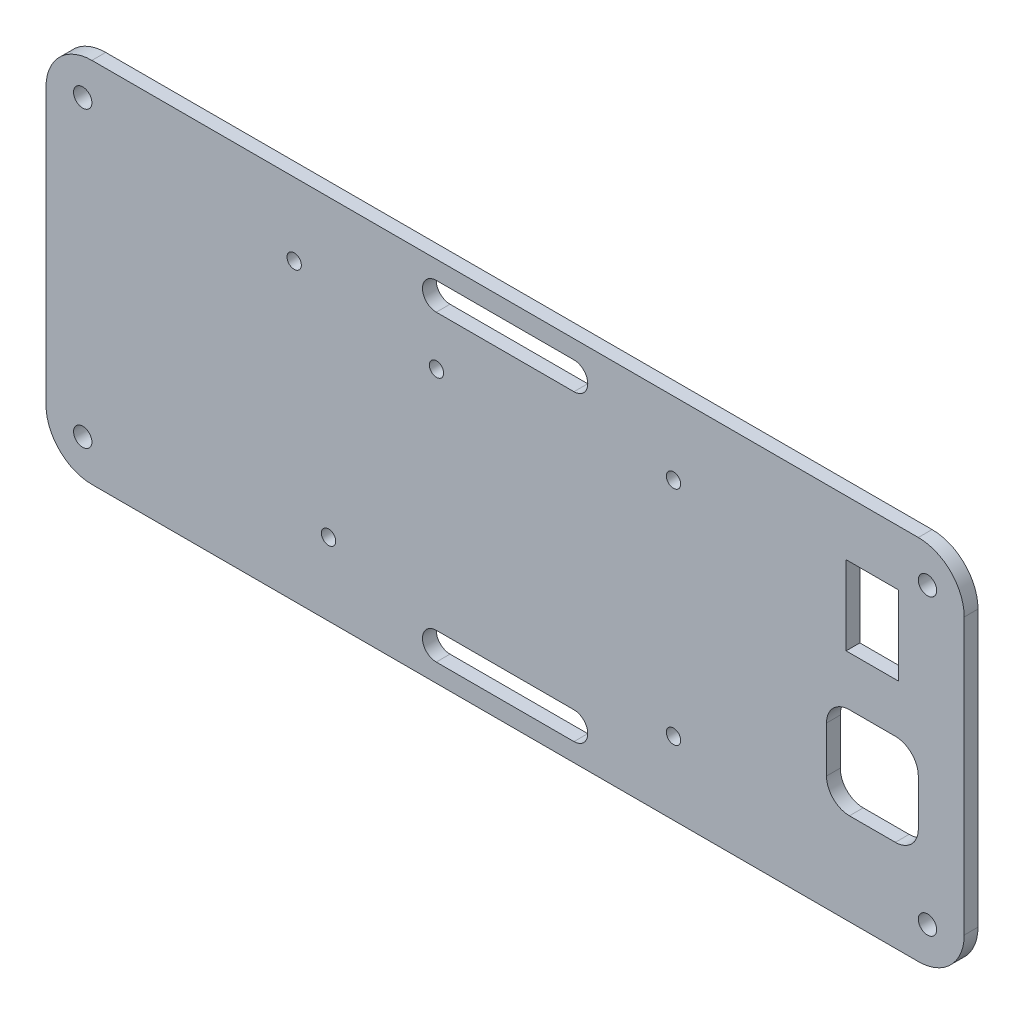
SolidWorks part; units mm, degrees
material "Mahogany"
ref_plane "Front Plane" through (0, 0, 0) normal (0, 0, 1) x (1, 0, 0)
ref_plane "Top Plane" through (0, 0, 0) normal (0, 1, 0) x (1, 0, 0)
ref_plane "Right Plane" through (0, 0, 0) normal (1, 0, 0) x (0, 0, -1)
sketch "Sketch1" plane through (0, 0, 0) normal (0, 0, 1) x (1, 0, 0)
  line L1 (-100, 40) -> (100, 40)
  line L2 (-100, 40) -> (-100, -40)
  line L3 (-100, -40) -> (100, -40)
  line L4 (100, 40) -> (100, -40)
  line L5 (-100, 40) -> (100, -40) construction
  line L6 (-100, -40) -> (100, 40) construction
  point P0 (0, 0)
  dimension "D1" = 80
  dimension "D2" = 200
extrude "Boss-Extrude1" add sketch "Sketch1" along normal blind 3
sketch "Sketch2" plane through (0, 0, 3) normal (0, 0, 1) x (1, 0, 0)
  line L0 (-100, 40) -> (-100, -40) construction
  line L1 (100, 40) -> (-100, 40) construction
  line L2 (0, 40) -> (0, -40) construction
  line L3 (-100, -40) -> (100, -40) construction
  line L4 (-100, 0) -> (100, 0) construction
  line L5 (100, -40) -> (100, 40) construction
  circle A0 centre (-92, 32) radius 2
  circle A1 centre (-92, -32) radius 2
  circle A2 centre (92, -32) radius 2
  circle A3 centre (92, 32) radius 2
  dimension "D1" = 4
  dimension "D2" = 8
  dimension "D3" = 8
extrude "Cut-Extrude1" cut sketch "Sketch2" against normal through all
fillet "Fillet1" radius 10 4 edges at (-100, -40, 1.5) (100, -40, 1.5) (100, 40, 1.5) (-100, 40, 1.5)
sketch "Sketch3" plane through (0, 0, 3) normal (0, 0, 1) x (1, 0, 0)
  circle A0 centre (36.6776, 24.1681) radius 1.5621
  circle A1 centre (36.6776, -24.1681) radius 1.5621
  circle A2 centre (-38.4556, -24.1681) radius 1.5621
  circle A3 centre (-45.9486, 24.1681) radius 1.5621
  circle A4 centre (-14.9479, 19.2896) radius 1.5621
extrude "Cut-Extrude2" cut sketch "Sketch3" against normal through all
sketch "Sketch4" plane through (0, 0, 3) normal (0, 0, 1) x (1, 0, 0)
  line L1 (70, 0) -> (90, 0)
  line L2 (70, 0) -> (70, -20)
  line L3 (70, -20) -> (90, -20)
  line L4 (90, 0) -> (90, -20)
  line L5 (70, 0) -> (90, -20) construction
  line L6 (70, -20) -> (90, 0) construction
  line L7 (100, -30) -> (100, 30) construction
  line L8 (-90, -40) -> (90, -40) construction
  point P0 (80, -10)
  dimension "D1" = 20
  dimension "D2" = 20
  dimension "D3" = 10
  dimension "D4" = 30
extrude "Cut-Extrude3" cut sketch "Sketch4" against normal through all
fillet "Fillet2" radius 5 4 edges at (90, -20, 1.5) (70, -20, 1.5) (70, 0, 1.5) (90, 0, 1.5)
sketch "Sketch5" plane through (0, 0, 3) normal (0, 0, 1) x (1, 0, 0)
  line L0 (-15, -33) -> (15, -33) construction
  line L1 (-15, -30) -> (15, -30)
  line L2 (-15, -36) -> (15, -36)
  line L3 (-90, -40) -> (90, -40) construction
  line L4 (-100, 0) -> (100, 0) construction
  line L5 (-100, 30) -> (-100, -30) construction
  line L6 (100, -30) -> (100, 30) construction
  line L7 (-15, 33) -> (15, 33) construction
  line L8 (-15, 30) -> (15, 30)
  line L9 (-15, 36) -> (15, 36)
  arc A0 (-15, -30) -> (-15, -36) centre (-15, -33) ccw
  arc A1 (15, -36) -> (15, -30) centre (15, -33) ccw
  arc A2 (-15, 30) -> (-15, 36) centre (-15, 33) cw
  arc A3 (15, 36) -> (15, 30) centre (15, 33) cw
  point P2 (0, -33)
  point P10 (0, -40)
  point P18 (0, 33)
  dimension "D2" = 3
  dimension "D1" = 7
  dimension "D3" = 30
extrude "Cut-Extrude4" cut sketch "Sketch5" against normal through all
sketch "Sketch6" plane through (0, 0, 3) normal (0, 0, 1) x (1, 0, 0)
  line L1 (74.275, 27.95) -> (85.725, 27.95)
  line L2 (74.275, 27.95) -> (74.275, 10.75)
  line L3 (74.275, 10.75) -> (85.725, 10.75)
  line L4 (85.725, 27.95) -> (85.725, 10.75)
extrude "Cut-Extrude5" cut sketch "Sketch6" against normal through all
